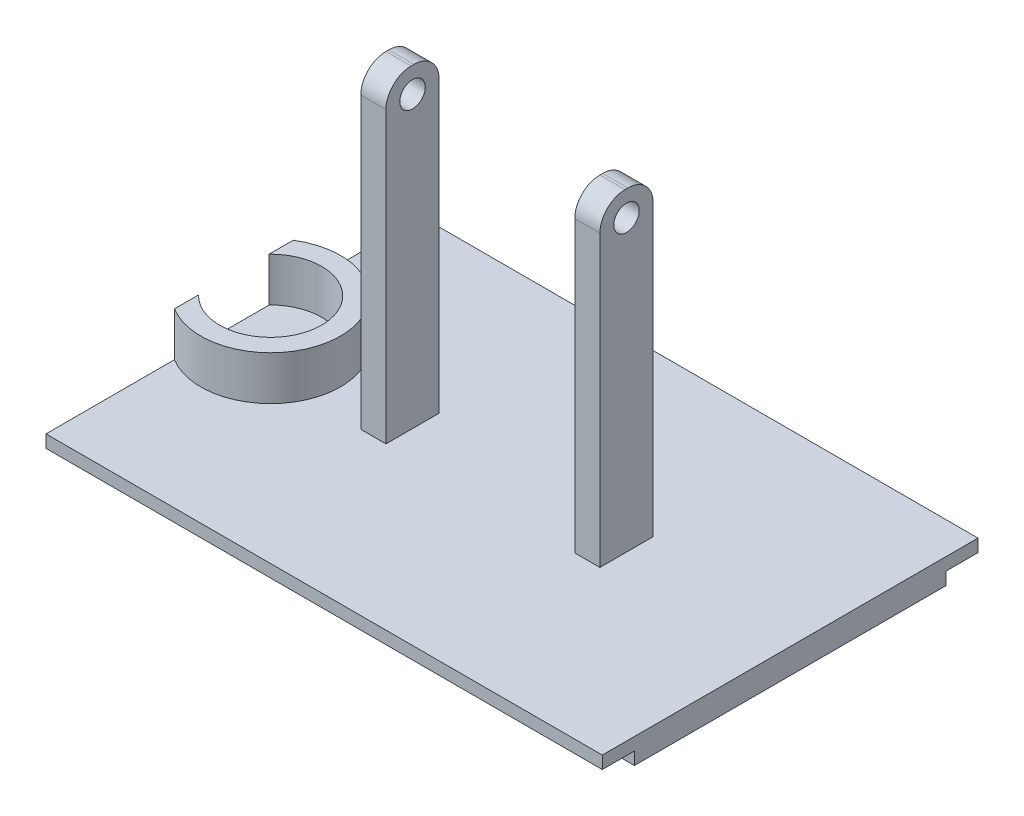
SolidWorks part; units mm, degrees
ref_plane "Ön Düzlem" through (0, 0, 0) normal (0, 0, 1) x (1, 0, 0)
ref_plane "Üst Düzlem" through (0, 0, 0) normal (0, 1, 0) x (1, 0, 0)
ref_plane "Sağ Düzlem" through (0, 0, 0) normal (1, 0, 0) x (0, 0, -1)
sketch "Çizim2" plane through (0, 0, 0) normal (0, 1, 0) x (1, 0, 0)
  line L0 (-38.4161, 0) -> (49.9739, 0)
  line L5 (49.9739, 0) -> (49.9739, -59.7)
  line L6 (49.9739, -59.7) -> (-38.4161, -59.7)
  line L7 (-38.4161, -59.7) -> (-38.4161, 0)
  dimension "D1" = 88.39
  dimension "D2" = 59.7
extrude "Yükseklik-Ekstrüzyon1" add sketch "Çizim2" along normal blind 4
sketch "Çizim3" plane through (0, 4, 0) normal (0, 1, 0) x (1, 0, 0)
  line L4 (-38.4161, 0) -> (-38.4161, -59.7)
  line L5 (-38.4161, -59.7) -> (49.9739, -59.7)
  line L6 (49.9739, -59.7) -> (49.9739, 0)
  line L7 (49.9739, 0) -> (-38.4161, 0)
  line L8 (-38.4161, 0) -> (-38.4161, -59.7)
  line L9 (-38.4161, -59.7) -> (49.9739, -59.7)
  line L10 (49.9739, -59.7) -> (49.9739, 0)
  line L11 (49.9739, 0) -> (-38.4161, 0)
  arc A0 (-38.4161, -35.461) -> (-38.4161, -24.239) centre (-32.5743, -29.85) ccw
  arc A1 (-38.4161, -39.2884) -> (-38.4161, -20.4116) centre (-32.5743, -29.85) ccw
  arc A2 (-40.5798, -37.5392) -> (-40.5798, -22.1608) centre (-32.5743, -29.85) ccw construction
  line M5 (-38.4161, 0) -> (-38.4161, -59.7)
  dimension "D2" = 3
  dimension "D1" = 0
extrude "Yükseklik-Ekstrüzyon2" add sketch "Çizim3" along normal blind 7 contours A1 L8 A0 M5
sketch "Çizim4" plane through (0, 4, 0) normal (0, 1, 0) x (1, 0, 0)
  line L5 (-38.4161, -39.2884) -> (-38.4161, -59.7)
  line L6 (-38.4161, -59.7) -> (49.9739, -59.7)
  line L7 (49.9739, -59.7) -> (49.9739, 0)
  line L8 (49.9739, 0) -> (-38.4161, 0)
  line L9 (-38.4161, 0) -> (-38.4161, -20.4116)
  line L10 (-38.4161, -39.2884) -> (-38.4161, -59.7)
  line L11 (-38.4161, -59.7) -> (49.9739, -59.7)
  line L12 (49.9739, -59.7) -> (49.9739, 0)
  line L13 (49.9739, 0) -> (-38.4161, 0)
  line L14 (-38.4161, 0) -> (-38.4161, -20.4116)
  arc A1 (-38.4161, -39.2884) -> (-38.4161, -20.4116) centre (-32.5743, -29.85) ccw
  arc A2 (-38.4161, -39.2884) -> (-38.4161, -20.4116) centre (-32.5743, -29.85) ccw
  dimension "D1" = 0
ref_plane "Düzlem1" through (19.9739, 0, 0) normal (1, 0, 0) x (0, 0, -1)
ref_plane "Düzlem2" through (-10.0261, 0, 0) normal (1, 0, 0) x (0, 0, -1)
sketch "Çizim5" plane through (19.9739, 0, 0) normal (1, 0, 0) x (0, 0, -1)
  line L0 (-32.0032, 4) -> (-27.6968, 4)
  line L1 (-18.75, 4) -> (-40.95, 4) construction
  line L2 (-34.0733, 4) -> (-34.0733, 54)
  line L3 (-34.0733, 54) -> (-25.6267, 54)
  line L4 (-25.6267, 54) -> (-25.6267, 4)
  line L5 (-32.0032, 4) -> (-34.0733, 4)
  line L7 (-27.6968, 4) -> (-25.6267, 4)
  dimension "D1" = 50
extrude "Yükseklik-Ekstrüzyon3" add sketch "Çizim5" along normal blind 4
fillet "Radyus2" radius 4 2 edges at (21.9739, 54, 34.0733) (21.9739, 54, 25.6267)
sketch "Çizim6" plane through (23.9739, 0, 0) normal (1, 0, 0) x (0, 0, -1)
  circle A0 centre (-29.85, 50) radius 2.025
  dimension "D1" = 4.05
extrude "Kes-Ekstrüzyon1" cut sketch "Çizim6" against normal blind 4
ref_plane "Düzlem3" through (4.9739, 0, 0) normal (1, 0, 0) x (0, 0, -1)
mirror "Aynalama1" about plane through (4.9739, 0, 0) normal (1, 0, 0) of "Kes-Ekstrüzyon1", "Yükseklik-Ekstrüzyon3", "Radyus2"
sketch "Çizim9" plane through (-38.4161, 0, 0) normal (-1, 0, 0) x (0, 0, 1)
  line L0 (0, 2) -> (4.9963, 2)
  line L12 (0, 0) -> (59.7, 0)
  line L13 (59.7, 0) -> (59.7, 4)
  line L14 (59.7, 4) -> (39.2884, 4)
  line L15 (39.2884, 4) -> (39.2884, 11)
  line L16 (39.2884, 11) -> (35.461, 11)
  line L17 (35.461, 11) -> (35.461, 4)
  line L18 (35.461, 4) -> (24.239, 4)
  line L19 (24.239, 4) -> (24.239, 11)
  line L20 (24.239, 11) -> (20.4116, 11)
  line L21 (20.4116, 11) -> (20.4116, 4)
  line L22 (20.4116, 4) -> (0, 4)
  line L23 (0, 4) -> (0, 0)
  line L24 (0, 0) -> (59.7, 0)
  line L25 (59.7, 0) -> (59.7, 4)
  line L26 (59.7, 4) -> (39.2884, 4)
  line L27 (39.2884, 4) -> (39.2884, 11)
  line L28 (39.2884, 11) -> (35.461, 11)
  line L29 (35.461, 11) -> (35.461, 4)
  line L30 (35.461, 4) -> (24.239, 4)
  line L31 (24.239, 4) -> (24.239, 11)
  line L32 (24.239, 11) -> (20.4116, 11)
  line L33 (20.4116, 11) -> (20.4116, 4)
  line L34 (20.4116, 4) -> (0, 4)
  line L35 (0, 4) -> (0, 0)
  dimension "D1" = 0
sketch "Çizim10" plane through (-38.4161, 0, 0) normal (-1, 0, 0) x (0, 0, 1)
  line L1 (0, 2) -> (5.1, 2)
  line L2 (59.7, 2) -> (54.6, 2)
  line L3 (5.1, 2) -> (5.1, 0)
  line L4 (54.6, 2) -> (54.6, 0)
  line L12 (0, 0) -> (59.7, 0)
  line L13 (59.7, 0) -> (59.7, 4)
  line L14 (59.7, 4) -> (39.2884, 4)
  line L15 (39.2884, 4) -> (39.2884, 11)
  line L16 (39.2884, 11) -> (35.461, 11)
  line L17 (35.461, 11) -> (35.461, 4)
  line L18 (35.461, 4) -> (24.239, 4)
  line L19 (24.239, 4) -> (24.239, 11)
  line L20 (24.239, 11) -> (20.4116, 11)
  line L21 (20.4116, 11) -> (20.4116, 4)
  line L22 (20.4116, 4) -> (0, 4)
  line L23 (0, 4) -> (0, 0)
  line L24 (0, 0) -> (59.7, 0)
  line L25 (59.7, 0) -> (59.7, 4)
  line L26 (59.7, 4) -> (39.2884, 4)
  line L27 (39.2884, 4) -> (39.2884, 11)
  line L28 (39.2884, 11) -> (35.461, 11)
  line L29 (35.461, 11) -> (35.461, 4)
  line L30 (35.461, 4) -> (24.239, 4)
  line L31 (24.239, 4) -> (24.239, 11)
  line L32 (24.239, 11) -> (20.4116, 11)
  line L33 (20.4116, 11) -> (20.4116, 4)
  line L34 (20.4116, 4) -> (0, 4)
  line L35 (0, 4) -> (0, 0)
  line M13 (0, 0) -> (59.7, 0)
  line M14 (59.7, 0) -> (59.7, 4)
  line M24 (0, 4) -> (0, 0)
  dimension "D2" = 5.1
  dimension "D3" = 5.1
  dimension "D1" = 0
extrude "Kes-Ekstrüzyon2" cut sketch "Çizim10" against normal up to surface (88.39 mm away) contours L3 L1 M24 M13 | L2 L4 M13 M14 up to face at (49.9739, 2, 29.85)
